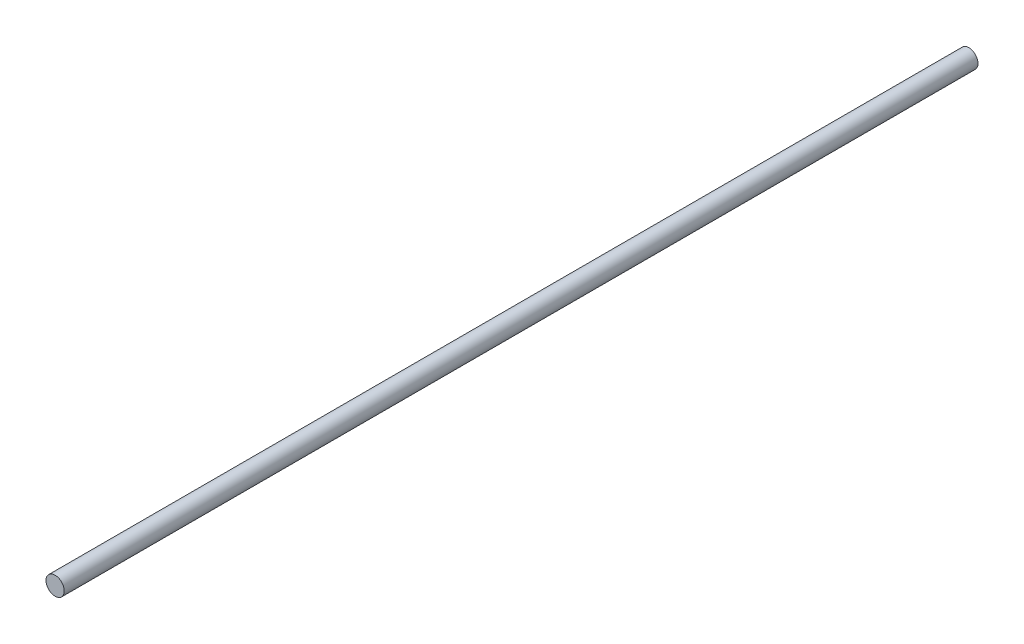
SolidWorks part; units mm, degrees
ref_plane "Plan de face" through (0, 0, 0) normal (0, 0, 1) x (1, 0, 0)
ref_plane "Plan de dessus" through (0, 0, 0) normal (0, 1, 0) x (1, 0, 0)
ref_plane "Plan de droite" through (0, 0, 0) normal (1, 0, 0) x (0, 0, -1)
sketch "Esquisse1" plane through (0, 0, 0) normal (0, 0, 1) x (1, 0, 0)
  circle A0 centre (-68.9316, -191.2267) radius 0.4
  dimension "D1" = 0.8
extrude "Boss.-Extru.1" add sketch "Esquisse1" against normal blind 40
